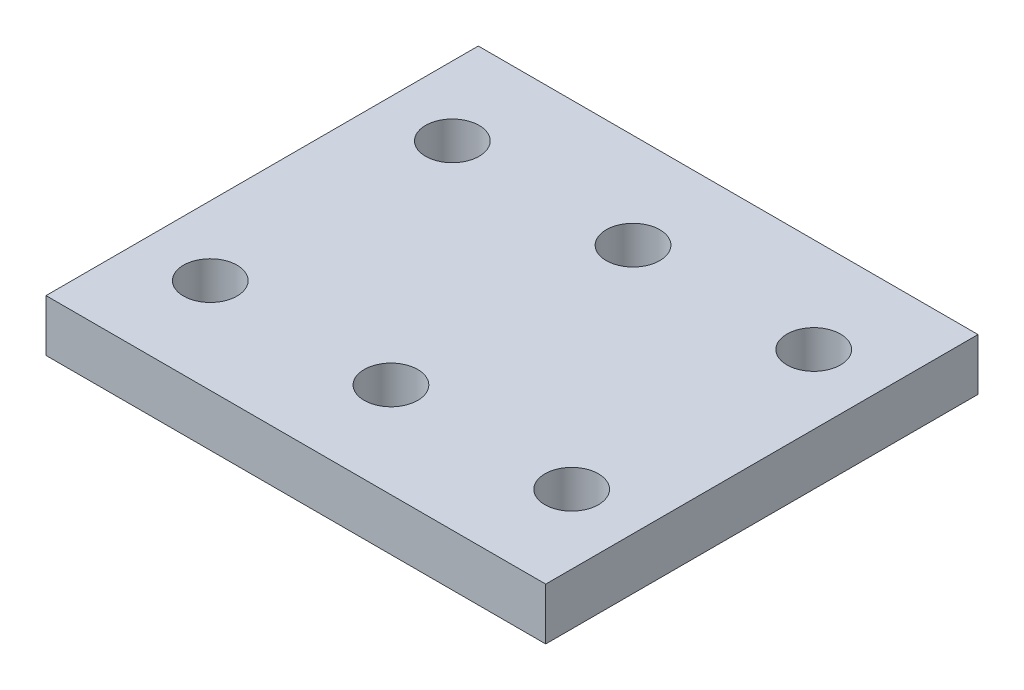
SolidWorks part; units mm, degrees
material "Thornel Mat VMA"
ref_plane "前视基准面" through (0, 0, 0) normal (0, 0, 1) x (1, 0, 0)
ref_plane "上视基准面" through (0, 0, 0) normal (0, 1, 0) x (1, 0, 0)
ref_plane "右视基准面" through (0, 0, 0) normal (1, 0, 0) x (0, 0, -1)
sketch "草图1" plane through (0, 0, 0) normal (0, 1, 0) x (1, 0, 0)
  line L0 (0, 0) -> (0, 13.0567) construction
  line L1 (14.45, -12.5) -> (-14.45, -12.5)
  line L2 (14.45, -12.5) -> (14.45, 12.5)
  line L3 (14.45, 12.5) -> (-14.45, 12.5)
  line L4 (-14.45, -12.5) -> (-14.45, 12.5)
  line L5 (14.45, -12.5) -> (-14.45, 12.5) construction
  line L6 (14.45, 12.5) -> (-14.45, -12.5) construction
  line L7 (10.45, -7) -> (-10.45, -7) construction
  line L8 (10.45, -7) -> (10.45, 7) construction
  line L9 (10.45, 7) -> (-10.45, 7) construction
  line L10 (-10.45, -7) -> (-10.45, 7) construction
  line L11 (10.45, -7) -> (-10.45, 7) construction
  line L12 (10.45, 7) -> (-10.45, -7) construction
  line L13 (0, 0) -> (14.3972, 0) construction
  circle A0 centre (10.45, 7) radius 1.55
  circle A1 centre (10.45, -7) radius 1.55
  circle A2 centre (-10.45, -7) radius 1.55
  circle A3 centre (-10.45, 7) radius 1.55
  circle A8 centre (0, 7) radius 1.55
  circle A9 centre (0, -7) radius 1.55
  point P0 (0, 0)
  point P6 (0, 0)
  dimension "D3" = 3.1
  dimension "D1" = 14
  dimension "D2" = 20.9
  dimension "D4" = 4
  dimension "D5" = 25
extrude "凸台-拉伸1" add sketch "草图1" along normal blind 3
